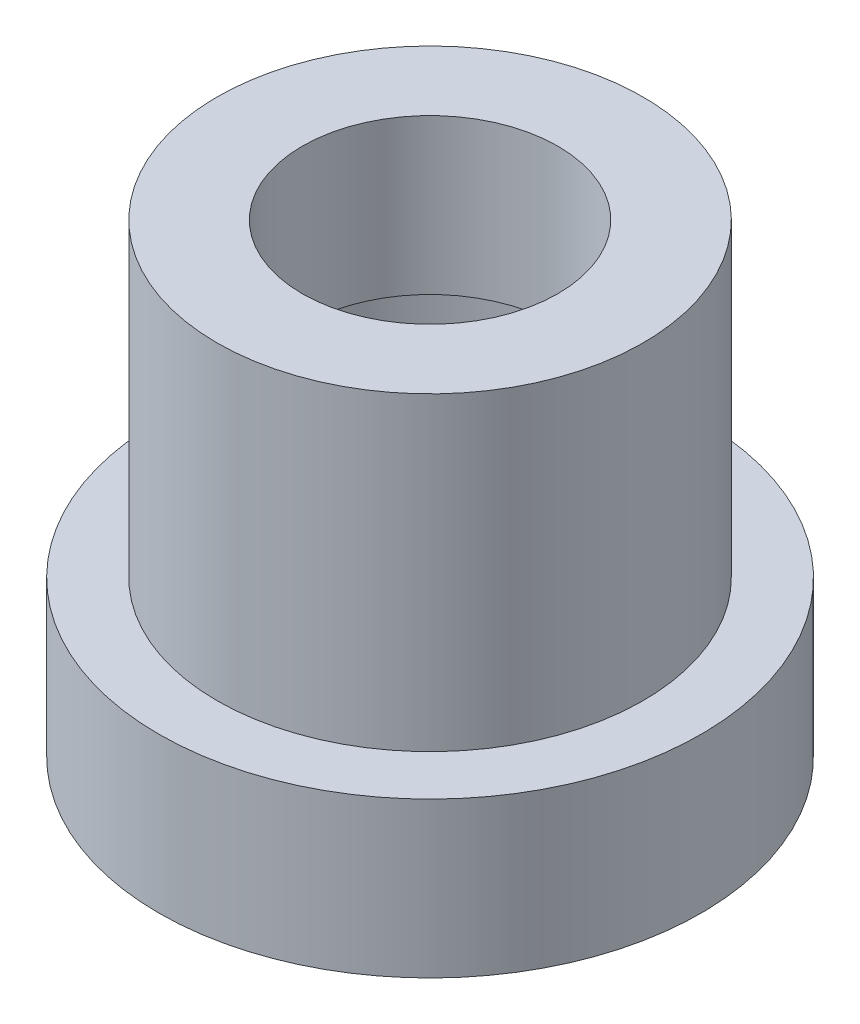
SolidWorks part; units mm, degrees
ref_plane "Front Plane" through (0, 0, 0) normal (0, 0, 1) x (1, 0, 0)
ref_plane "Top Plane" through (0, 0, 0) normal (0, 1, 0) x (1, 0, 0)
ref_plane "Right Plane" through (0, 0, 0) normal (1, 0, 0) x (0, 0, -1)
sketch "Sketch3" plane through (0, 0, 0) normal (0, 1, 0) x (1, 0, 0)
  circle A0 centre (0, 0) radius 3.5
  circle A1 centre (0, 0) radius 2.5
  dimension "D1" = 7
  dimension "D2" = 5
extrude "Boss-Extrude3" add sketch "Sketch3" along normal blind 2
sketch "Sketch4" plane through (0, 2, 0) normal (0, 1, 0) x (1, 0, 0)
  circle A0 centre (0, 0) radius 1.65
  circle A1 centre (0, 0) radius 2.75
  dimension "D1" = 3.3
  dimension "D2" = 5.5
extrude "Boss-Extrude4" add sketch "Sketch4" along normal blind 4
sketch "Sketch5" plane through (0, 2, 0) normal (0, -1, 0) x (1, 0, 0)
  circle A1 centre (0, 0) radius 2.5
  circle A2 centre (0, 0) radius 2.5
  dimension "D1" = 0
extrude "Cut-Extrude1" cut sketch "Sketch5" against normal blind 2
